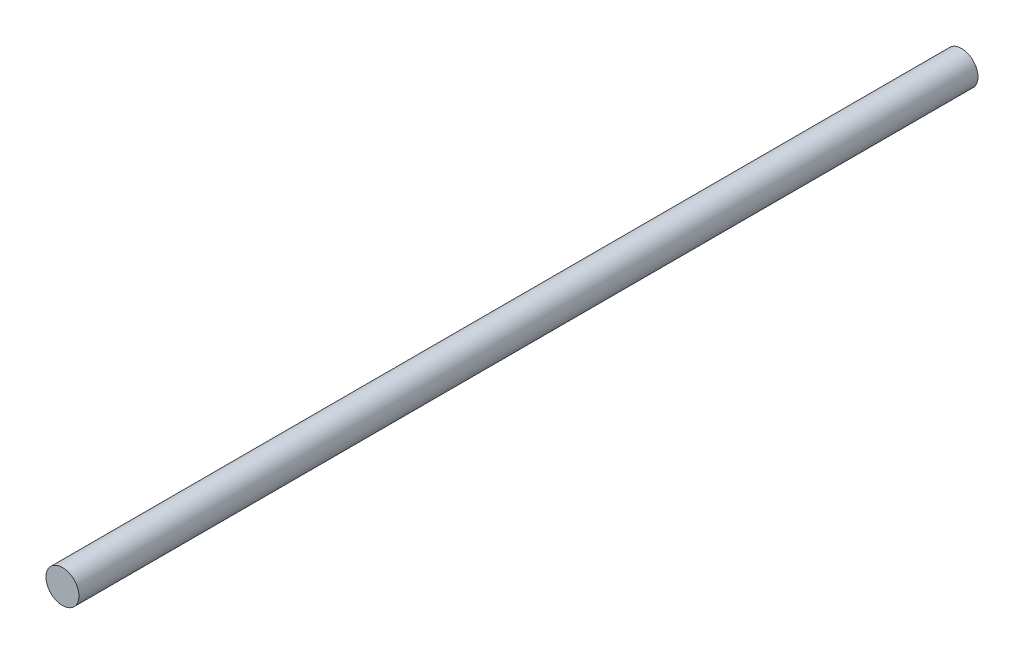
SolidWorks part; units mm, degrees
ref_plane "正面" through (0, 0, 0) normal (0, 0, 1) x (1, 0, 0)
ref_plane "平面" through (0, 0, 0) normal (0, 1, 0) x (1, 0, 0)
ref_plane "右側面" through (0, 0, 0) normal (1, 0, 0) x (0, 0, -1)
sketch "ｽｹｯﾁ1" plane through (0, 0, 0) normal (0, 0, 1) x (1, 0, 0)
  circle A0 centre (0, 0) radius 2.75
  dimension "D1" = 5.5
extrude "ﾎﾞｽ - 押し出し1" add sketch "ｽｹｯﾁ1" along normal blind 150
